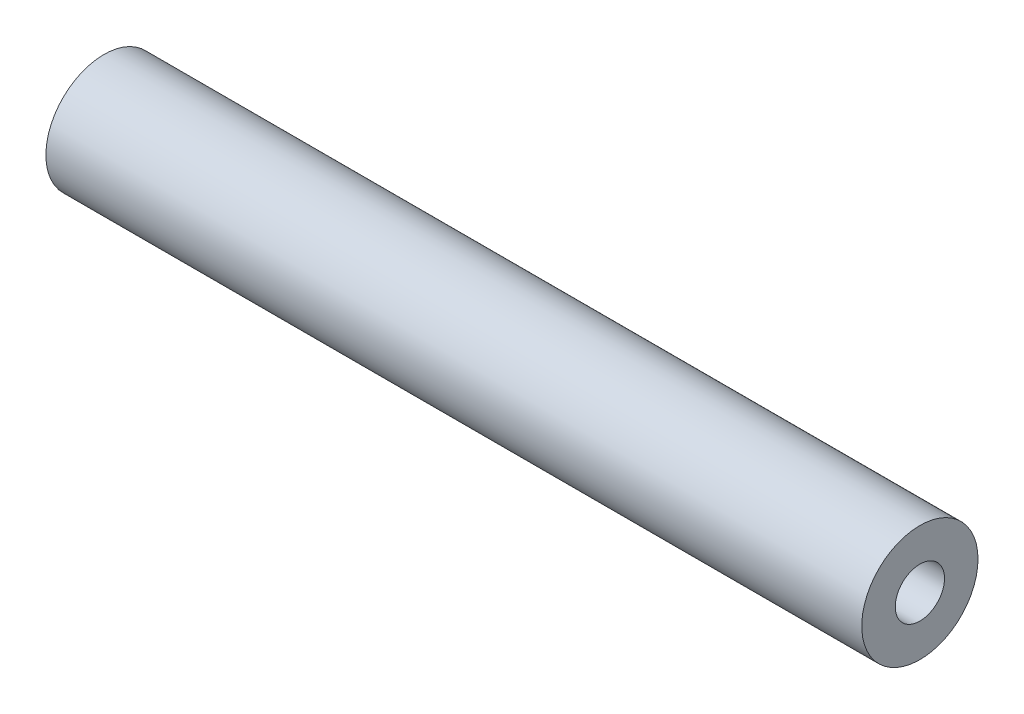
SolidWorks part; units mm, degrees
ref_plane "Front Plane" through (0, 0, 0) normal (0, 0, 1) x (1, 0, 0)
ref_plane "Top Plane" through (0, 0, 0) normal (0, 1, 0) x (1, 0, 0)
ref_plane "Right Plane" through (0, 0, 0) normal (1, 0, 0) x (0, 0, -1)
sketch "Sketch1" plane through (0, 0, 0) normal (1, 0, 0) x (0, 0, -1)
  circle A0 centre (0, 0) radius 2.0193
  circle A1 centre (0, 0) radius 4.7625
  dimension "D1" = 4.0386
  dimension "D2" = 9.525
extrude "Boss-Extrude1" add sketch "Sketch1" along normal blind 66.854
